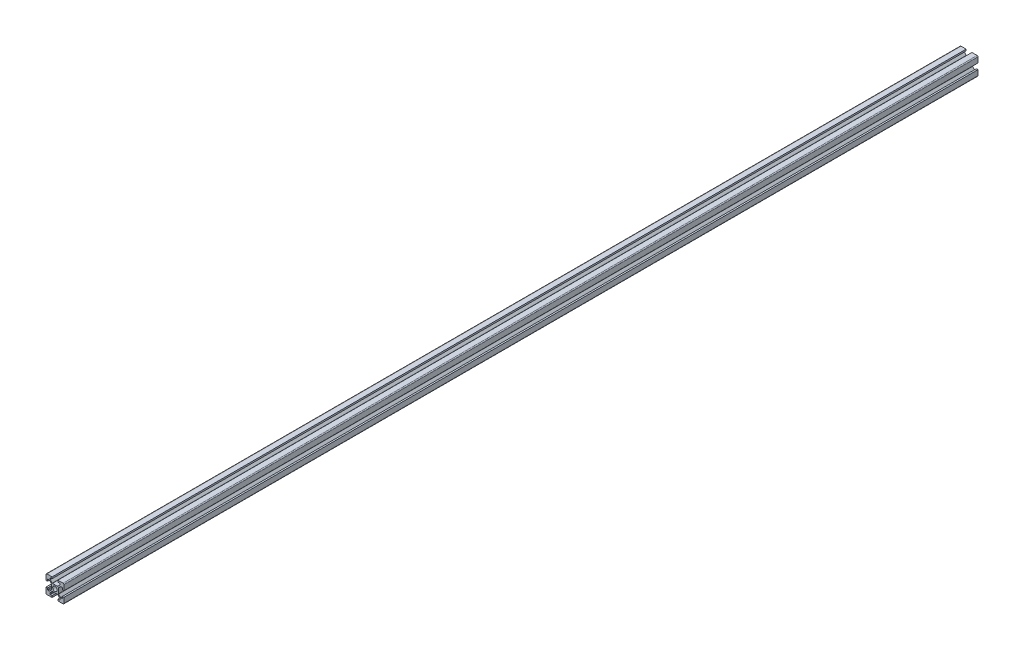
SolidWorks part; units mm, degrees
material "1060 Alloy"
ref_plane "Front Plane" through (0, 0, 0) normal (0, 0, 1) x (1, 0, 0)
ref_plane "Top Plane" through (0, 0, 0) normal (0, 1, 0) x (1, 0, 0)
ref_plane "Right Plane" through (0, 0, 0) normal (1, 0, 0) x (0, 0, -1)
sketch "Sketch1" plane through (0, 0, 0) normal (0, 0, 1) x (1, 0, 0)
  line L0 (20, 0) -> (-8.059, 28.059) construction
  line L1 (0, 0) -> (6.8, 0)
  line L2 (0, 0) -> (0, 6.8)
  line L3 (0, 20) -> (6.8, 20)
  line L4 (20, 0) -> (20, 6.8)
  line L5 (6.8, 20) -> (6.8, 18.2)
  line L6 (20, 20) -> (8.2322, 8.2322) construction
  line L7 (12.95, 6.1) -> (7.05, 6.1)
  line L8 (13.9, 7.05) -> (13.9, 12.95)
  line L9 (12.95, 13.9) -> (7.05, 13.9)
  line L10 (6.1, 7.05) -> (6.1, 12.95)
  line L11 (13.9, 6.1) -> (6.1, 13.9) construction
  line L12 (13.9, 13.9) -> (6.1, 6.1) construction
  line L13 (4.55, 16.4) -> (7.05, 13.9)
  line L14 (13.2, 18.2) -> (13.2, 20)
  line L15 (1.8, 6.8) -> (0, 6.8)
  line L16 (0, 13.2) -> (0, 20)
  line L17 (0, 13.2) -> (1.8, 13.2)
  line L18 (10, 10) -> (10, 13.9) construction
  line L19 (16.4, 4.55) -> (13.9, 7.05)
  line L20 (4.55, 16.4) -> (4.55, 18.2)
  line L21 (4.55, 18.2) -> (6.8, 18.2)
  line L22 (13.2, 18.2) -> (15.45, 18.2)
  line L23 (15.45, 18.2) -> (15.45, 16.4)
  line L24 (15.45, 16.4) -> (12.95, 13.9)
  line L25 (16.4, 4.55) -> (18.2, 4.55)
  line L26 (18.2, 4.55) -> (18.2, 6.8)
  line L27 (20, 6.8) -> (18.2, 6.8)
  line L28 (18.2, 13.2) -> (20, 13.2)
  line L29 (18.2, 13.2) -> (18.2, 15.45)
  line L30 (18.2, 15.45) -> (16.4, 15.45)
  line L31 (16.4, 15.45) -> (13.9, 12.95)
  line L32 (1.8, 4.55) -> (3.6, 4.55)
  line L33 (3.6, 15.45) -> (6.1, 12.95)
  line L34 (3.6, 15.45) -> (1.8, 15.45)
  line L35 (1.8, 15.45) -> (1.8, 13.2)
  line L36 (0, 13.2) -> (1.8, 13.2)
  line L37 (1.8, 6.8) -> (0, 6.8)
  line L38 (3.6, 4.55) -> (6.1, 7.05)
  line L39 (1.8, 6.8) -> (1.8, 4.55)
  line L40 (15.45, 3.6) -> (12.95, 6.1)
  line L41 (4.55, 3.6) -> (7.05, 6.1)
  line L42 (4.55, 1.8) -> (4.55, 3.6)
  line L43 (6.8, 1.8) -> (4.55, 1.8)
  line L44 (6.8, 1.8) -> (6.8, 0)
  line L45 (15.45, 3.6) -> (15.45, 1.8)
  line L46 (15.45, 1.8) -> (13.2, 1.8)
  line L47 (13.2, 0) -> (13.2, 1.8)
  line L48 (13.2, 20) -> (20, 20)
  line L49 (20, 13.2) -> (20, 20)
  line L50 (13.2, 0) -> (20, 0)
  line L51 (6.1, 6.1) -> (-5.5045, -5.5045) construction
  circle A0 centre (10, 10) radius 2.5
  point P25 (10, 16.4)
  point P39 (13.2, 19.1)
  point P46 (0.9, 6.8)
  dimension "D3" = 5
  dimension "D2" = 20
  dimension "D4" = 7.8
  dimension "D5" = 7.8
  dimension "D6" = 6.8
  dimension "D7" = 6.8
  dimension "D8" = 1.8
  dimension "D9" = 10.9
  dimension "D10" = 1.8
  dimension "D11" = 10.9
  dimension "D12" = 20
extrude "Boss-Extrude1" add sketch "Sketch1" along normal blind 1020 contours L47 L50 L4 L27 L26 L25 L19 L8 L31 L30 L29 L28 L49 L48 L14 L22 L23 L24 L9 L13 L20 L21 L5 L3 L16 L17 L35 L34 L33 L10 L38 L32 L39 L15 L2 L1 L44 L43 L42 L41 L7 L40 L45 L46 A0
fillet "Fillet1" radius 1 4 edges at (20, 20, 510) (20, 0, 510) (0, 0, 510) (0, 20, 510)
fillet "Fillet2" radius 0.5 6 edges at (4.55, 18.2, 510) (4.55, 16.4, 510) (7.05, 13.9, 510) (15.45, 18.2, 510) (15.45, 16.4, 510) (12.95, 13.9, 510)
fillet "Fillet3" radius 0.5 6 edges at (18.2, 15.45, 510) (16.4, 15.45, 510) (13.9, 12.95, 510) (18.2, 4.55, 510) (13.9, 7.05, 510) (16.4, 4.55, 510)
fillet "Fillet4" radius 0.5 6 edges at (1.8, 15.45, 510) (3.6, 15.45, 510) (6.1, 12.95, 510) (3.6, 4.55, 510) (1.8, 4.55, 510) (6.1, 7.05, 510)
fillet "Fillet5" radius 0.5 6 edges at (7.05, 6.1, 510) (4.55, 3.6, 510) (4.55, 1.8, 510) (15.45, 1.8, 510) (15.45, 3.6, 510) (12.95, 6.1, 510)
